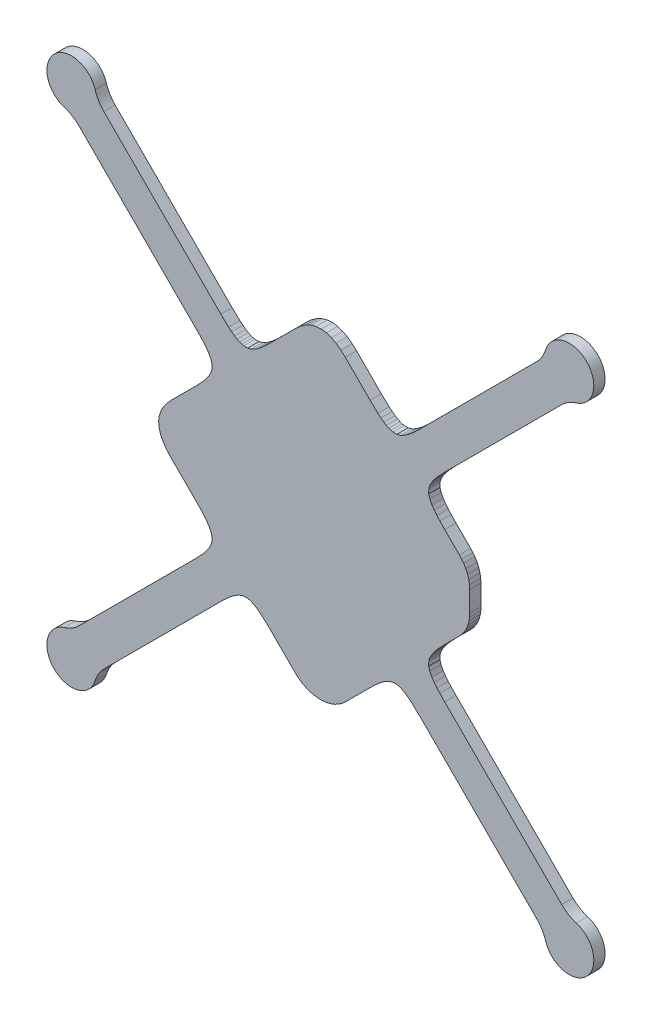
SolidWorks part; units mm, degrees
ref_plane "Ebene vorne" through (0, 0, 0) normal (0, 0, 1) x (1, 0, 0)
ref_plane "Ebene oben" through (0, 0, 0) normal (0, 1, 0) x (1, 0, 0)
ref_plane "Ebene rechts" through (0, 0, 0) normal (1, 0, 0) x (0, 0, -1)
sketch "Sketch1" plane through (0, 0, 0) normal (0, 0, 1) x (1, 0, 0)
  line L0 (-34.5399, 35.1422) -> (-35.5879, 34.0297)
  line L1 (-34.1889, 35.565) -> (-34.5399, 35.1422)
  line L2 (-33.8749, 35.9932) -> (-34.1889, 35.565)
  line L3 (-33.6599, 36.3364) -> (-33.8749, 35.9932)
  line L4 (-33.4859, 36.6836) -> (-33.6599, 36.3364)
  line L5 (-33.3769, 36.9817) -> (-33.4859, 36.6836)
  line L6 (-33.3109, 37.2818) -> (-33.3769, 36.9817)
  line L7 (-33.3089, 37.8363) -> (-33.3109, 37.2818)
  line L8 (-33.4609, 38.3866) -> (-33.3089, 37.8363)
  line L9 (-33.7639, 38.9678) -> (-33.4609, 38.3866)
  line L10 (-34.0939, 39.4424) -> (-33.7639, 38.9678)
  line L11 (-34.4729, 39.9107) -> (-34.0939, 39.4424)
  line L12 (-34.8849, 40.3729) -> (-34.4729, 39.9107)
  line L13 (-35.5879, 41.1007) -> (-34.8849, 40.3729)
  line L14 (-35.5879, 34.0297) -> (-39.1229, 30.4942)
  line L15 (-39.7409, 24.1062) -> (-39.1229, 23.4232)
  line L16 (-40.2589, 24.8442) -> (-39.7409, 24.1062)
  line L17 (-40.4699, 25.2332) -> (-40.2589, 24.8442)
  line L18 (-40.6419, 25.6332) -> (-40.4699, 25.2332)
  line L19 (-40.8379, 26.3492) -> (-40.6419, 25.6332)
  line L20 (-40.8889, 27.0812) -> (-40.8379, 26.3492)
  line L21 (-40.7889, 27.8092) -> (-40.8889, 27.0812)
  line L22 (-40.5479, 28.5142) -> (-40.7889, 27.8092)
  line L23 (-40.1889, 29.1862) -> (-40.5479, 28.5142)
  line L24 (-39.6979, 29.8632) -> (-40.1889, 29.1862)
  line L25 (-39.1229, 30.4942) -> (-39.6979, 29.8632)
  line L26 (-35.5879, 19.8872) -> (-39.1229, 23.4232)
  line L27 (-34.5399, 13.9292) -> (-35.5879, 12.8162)
  line L28 (-34.1889, 14.3522) -> (-34.5399, 13.9292)
  line L29 (-33.8749, 14.7802) -> (-34.1889, 14.3522)
  line L30 (-33.6599, 15.1232) -> (-33.8749, 14.7802)
  line L31 (-33.4859, 15.4702) -> (-33.6599, 15.1232)
  line L32 (-33.3769, 15.7682) -> (-33.4859, 15.4702)
  line L33 (-33.3109, 16.0682) -> (-33.3769, 15.7682)
  line L34 (-33.3089, 16.6232) -> (-33.3109, 16.0682)
  line L35 (-33.4609, 17.1732) -> (-33.3089, 16.6232)
  line L36 (-33.7639, 17.7542) -> (-33.4609, 17.1732)
  line L37 (-34.0939, 18.2292) -> (-33.7639, 17.7542)
  line L38 (-34.4729, 18.6972) -> (-34.0939, 18.2292)
  line L39 (-34.8849, 19.1602) -> (-34.4729, 18.6972)
  line L40 (-35.5879, 19.8872) -> (-34.8849, 19.1602)
  line L41 (-26.0929, 10.3282) -> (-24.9809, 9.2812)
  line L42 (-26.5159, 10.6792) -> (-26.0929, 10.3282)
  line L43 (-26.9439, 10.9942) -> (-26.5159, 10.6792)
  line L44 (-27.2879, 11.2082) -> (-26.9439, 10.9942)
  line L45 (-27.6349, 11.3822) -> (-27.2879, 11.2082)
  line L46 (-27.9329, 11.4912) -> (-27.6349, 11.3822)
  line L47 (-28.2329, 11.5582) -> (-27.9329, 11.4912)
  line L48 (-28.7879, 11.5602) -> (-28.2329, 11.5582)
  line L49 (-29.3379, 11.4072) -> (-28.7879, 11.5602)
  line L50 (-29.9189, 11.1042) -> (-29.3379, 11.4072)
  line L51 (-30.3939, 10.7742) -> (-29.9189, 11.1042)
  line L52 (-30.8619, 10.3952) -> (-30.3939, 10.7742)
  line L53 (-31.3239, 9.9832) -> (-30.8619, 10.3952)
  line L54 (-32.0519, 9.2812) -> (-31.3239, 9.9832)
  line L55 (-21.4455, 5.7457) -> (-24.9809, 9.2812)
  line L56 (-14.3744, 5.7457) -> (-10.8389, 9.2812)
  line L57 (-4.8799, 10.3282) -> (-3.7679, 9.2812)
  line L58 (-5.3029, 10.6792) -> (-4.8799, 10.3282)
  line L59 (-5.7309, 10.9942) -> (-5.3029, 10.6792)
  line L60 (-6.0739, 11.2082) -> (-5.7309, 10.9942)
  line L61 (-6.4219, 11.3822) -> (-6.0739, 11.2082)
  line L62 (-6.7199, 11.4912) -> (-6.4219, 11.3822)
  line L63 (-7.0199, 11.5582) -> (-6.7199, 11.4912)
  line L64 (-7.5739, 11.5602) -> (-7.0199, 11.5582)
  line L65 (-8.1249, 11.4072) -> (-7.5739, 11.5602)
  line L66 (-8.7059, 11.1042) -> (-8.1249, 11.4072)
  line L67 (-9.1809, 10.7742) -> (-8.7059, 11.1042)
  line L68 (-9.6489, 10.3952) -> (-9.1809, 10.7742)
  line L69 (-10.1109, 9.9832) -> (-9.6489, 10.3952)
  line L70 (-10.8389, 9.2812) -> (-10.1109, 9.9832)
  line L71 (-1.2799, 39.9882) -> (-0.2319, 41.1007)
  line L72 (-1.6309, 39.5654) -> (-1.2799, 39.9882)
  line L73 (-1.9449, 39.1372) -> (-1.6309, 39.5654)
  line L74 (-2.1589, 38.794) -> (-1.9449, 39.1372)
  line L75 (-2.3329, 38.4468) -> (-2.1589, 38.794)
  line L76 (-2.4419, 38.1487) -> (-2.3329, 38.4468)
  line L77 (-2.5089, 37.8486) -> (-2.4419, 38.1487)
  line L78 (-2.5109, 37.2941) -> (-2.5089, 37.8486)
  line L79 (-2.3589, 36.7438) -> (-2.5109, 37.2941)
  line L80 (-2.0559, 36.1626) -> (-2.3589, 36.7438)
  line L81 (-1.7259, 35.6879) -> (-2.0559, 36.1626)
  line L82 (-1.3469, 35.2197) -> (-1.7259, 35.6879)
  line L83 (-0.9349, 34.7575) -> (-1.3469, 35.2197)
  line L84 (-0.2319, 34.0297) -> (-0.9349, 34.7575)
  line L85 (-20.7619, 48.7893) -> (-21.4449, 48.1718)
  line L86 (-20.0239, 49.3073) -> (-20.7619, 48.7893)
  line L87 (-19.6359, 49.5183) -> (-20.0239, 49.3073)
  line L88 (-19.2349, 49.6911) -> (-19.6359, 49.5183)
  line L89 (-18.5199, 49.887) -> (-19.2349, 49.6911)
  line L90 (-17.7879, 49.9375) -> (-18.5199, 49.887)
  line L91 (-17.0599, 49.8374) -> (-17.7879, 49.9375)
  line L92 (-16.3539, 49.5972) -> (-17.0599, 49.8374)
  line L93 (-15.6819, 49.2379) -> (-16.3539, 49.5972)
  line L94 (-15.0059, 48.7468) -> (-15.6819, 49.2379)
  line L95 (-14.3739, 48.1718) -> (-15.0059, 48.7468)
  line L96 (-21.4449, 48.1718) -> (-24.9809, 44.6363)
  line L97 (-30.9399, 43.5886) -> (-32.0519, 44.6363)
  line L98 (-30.5169, 43.238) -> (-30.9399, 43.5886)
  line L99 (-30.0889, 42.9234) -> (-30.5169, 43.238)
  line L100 (-29.7449, 42.7091) -> (-30.0889, 42.9234)
  line L101 (-29.3979, 42.535) -> (-29.7449, 42.7091)
  line L102 (-29.0999, 42.4262) -> (-29.3979, 42.535)
  line L103 (-28.7999, 42.3592) -> (-29.0999, 42.4262)
  line L104 (-28.2449, 42.3574) -> (-28.7999, 42.3592)
  line L105 (-27.6949, 42.5099) -> (-28.2449, 42.3574)
  line L106 (-27.1139, 42.8128) -> (-27.6949, 42.5099)
  line L107 (-26.6389, 43.1429) -> (-27.1139, 42.8128)
  line L108 (-26.1709, 43.5218) -> (-26.6389, 43.1429)
  line L109 (-25.7089, 43.9338) -> (-26.1709, 43.5218)
  line L110 (-24.9809, 44.6363) -> (-25.7089, 43.9338)
  line L111 (-1.2799, 18.7752) -> (-0.2319, 19.8872)
  line L112 (-1.6309, 18.3522) -> (-1.2799, 18.7752)
  line L113 (-1.9449, 17.9242) -> (-1.6309, 18.3522)
  line L114 (-2.1589, 17.5812) -> (-1.9449, 17.9242)
  line L115 (-2.3329, 17.2332) -> (-2.1589, 17.5812)
  line L116 (-2.4419, 16.9352) -> (-2.3329, 17.2332)
  line L117 (-2.5089, 16.6352) -> (-2.4419, 16.9352)
  line L118 (-2.5109, 16.0812) -> (-2.5089, 16.6352)
  line L119 (-2.3589, 15.5302) -> (-2.5109, 16.0812)
  line L120 (-2.0559, 14.9492) -> (-2.3589, 15.5302)
  line L121 (-1.7259, 14.4752) -> (-2.0559, 14.9492)
  line L122 (-1.3469, 14.0062) -> (-1.7259, 14.4752)
  line L123 (-0.9349, 13.5442) -> (-1.3469, 14.0062)
  line L124 (-0.2319, 12.8162) -> (-0.9349, 13.5442)
  line L125 (-14.3739, 48.1718) -> (-10.8389, 44.6363)
  line L126 (-9.7259, 43.5886) -> (-10.8389, 44.6363)
  line L127 (-9.3029, 43.238) -> (-9.7259, 43.5886)
  line L128 (-8.8749, 42.9234) -> (-9.3029, 43.238)
  line L129 (-8.5319, 42.7091) -> (-8.8749, 42.9234)
  line L130 (-8.1849, 42.535) -> (-8.5319, 42.7091)
  line L131 (-7.8869, 42.4262) -> (-8.1849, 42.535)
  line L132 (-7.5869, 42.3592) -> (-7.8869, 42.4262)
  line L133 (-7.0319, 42.3574) -> (-7.5869, 42.3592)
  line L134 (-6.4819, 42.5099) -> (-7.0319, 42.3574)
  line L135 (-5.9009, 42.8128) -> (-6.4819, 42.5099)
  line L136 (-5.4259, 43.1429) -> (-5.9009, 42.8128)
  line L137 (-4.9579, 43.5218) -> (-5.4259, 43.1429)
  line L138 (-4.4959, 43.9338) -> (-4.9579, 43.5218)
  line L139 (-3.7679, 44.6363) -> (-4.4959, 43.9338)
  line L140 (-0.2319, 19.8872) -> (1.8391, 21.9582)
  line L141 (3.2841, 25.0252) -> (3.3031, 25.4942)
  line L142 (3.2251, 24.5682) -> (3.2841, 25.0252)
  line L143 (3.0831, 23.9782) -> (3.2251, 24.5682)
  line L144 (2.8681, 23.4162) -> (3.0831, 23.9782)
  line L145 (2.5811, 22.8852) -> (2.8681, 23.4162)
  line L146 (2.2401, 22.4052) -> (2.5811, 22.8852)
  line L147 (1.8391, 21.9582) -> (2.2401, 22.4052)
  line L148 (-0.2319, 34.0297) -> (1.8391, 31.9582)
  line L149 (3.3031, 28.4232) -> (3.3031, 25.4942)
  line L150 (2.1571, 31.6132) -> (1.8391, 31.9582)
  line L151 (2.4381, 31.2482) -> (2.1571, 31.6132)
  line L152 (2.7551, 30.7312) -> (2.4381, 31.2482)
  line L153 (3.0001, 30.1812) -> (2.7551, 30.7312)
  line L154 (3.1731, 29.6032) -> (3.0001, 30.1812)
  line L155 (3.2711, 29.0232) -> (3.1731, 29.6032)
  line L156 (3.3031, 28.4232) -> (3.2711, 29.0232)
  line L157 (-48.6686, -7.3359) -> (-32.0519, 9.2812)
  line L158 (-35.5879, 12.8162) -> (-52.205, -3.8004)
  line L159 (12.8487, -7.3359) -> (-3.7679, 9.2812)
  line L160 (-0.2319, 12.8162) -> (16.3851, -3.8004)
  line L161 (16.3851, 57.7176) -> (-0.2319, 41.1007)
  line L162 (-3.7679, 44.6363) -> (12.8487, 61.2535)
  line L163 (-48.6686, 61.2535) -> (-32.0519, 44.6363)
  line L164 (-35.5879, 41.1007) -> (-52.205, 57.7176)
  arc A0 (-21.4455, 5.7457) -> (-14.3744, 5.7457) centre (-17.9099, 9.2812) ccw
  arc A1 (-54.284, -5.0484) -> (-49.9166, -9.4158) centre (-53.2649, -8.3968) ccw
  arc A2 (-48.6686, -7.3359) -> (-49.9166, -9.4158) centre (-45.1991, -10.8319) ccw
  arc A3 (-54.284, -5.0484) -> (-52.205, -3.8004) centre (-55.7015, -0.3313) ccw
  arc A4 (14.0967, -9.4158) -> (18.4641, -5.0484) centre (17.4451, -8.3968) ccw
  arc A5 (14.0967, -9.4158) -> (12.8487, -7.3359) centre (9.3792, -10.8319) ccw
  arc A6 (16.3851, -3.8004) -> (18.4641, -5.0484) centre (19.8816, -0.3313) ccw
  arc A7 (18.4641, 58.9656) -> (14.0967, 63.333) centre (17.4451, 62.3139) ccw
  arc A8 (18.4641, 58.9656) -> (16.3851, 57.7176) centre (19.8816, 54.2485) ccw
  arc A9 (12.8487, 61.2535) -> (14.0967, 63.333) centre (9.3794, 64.7498) ccw
  arc A10 (-49.9166, 63.333) -> (-54.284, 58.9656) centre (-53.2649, 62.3139) ccw
  arc A11 (-49.9166, 63.333) -> (-48.6686, 61.2535) centre (-45.1993, 64.7498) ccw
  arc A12 (-52.205, 57.7176) -> (-54.284, 58.9656) centre (-55.7015, 54.2485) ccw
  point P57 (-14.3743, 5.7457)
  point P61 (-49.9166, -9.4158)
  point P168 (0, 0)
  point P171 (0, 0)
  point P172 (-48.6686, -7.3359)
  point P174 (-52.205, -3.8003)
  point P179 (16.3852, -3.8005)
  point P181 (12.8487, -7.3358)
  point P183 (14.0966, 63.333)
  point P186 (14.0966, -9.4158)
  point P190 (-49.9166, 63.333)
  point P192 (16.3851, 57.7176)
  point P194 (0, 0)
  point P197 (12.8487, 61.2534)
  point P198 (0, 0)
  point P203 (-48.6684, 61.2535)
  point P207 (-52.205, 57.7176)
  point P209 (0, 0)
  point P210 (-21.4455, 5.7457)
  point P211 (-52.2044, -3.801)
  point P212 (0, 0)
  point P213 (-52.2049, -3.8004)
extrude "Boss-Extrude1" add sketch "Sketch1" along normal blind 1.6
